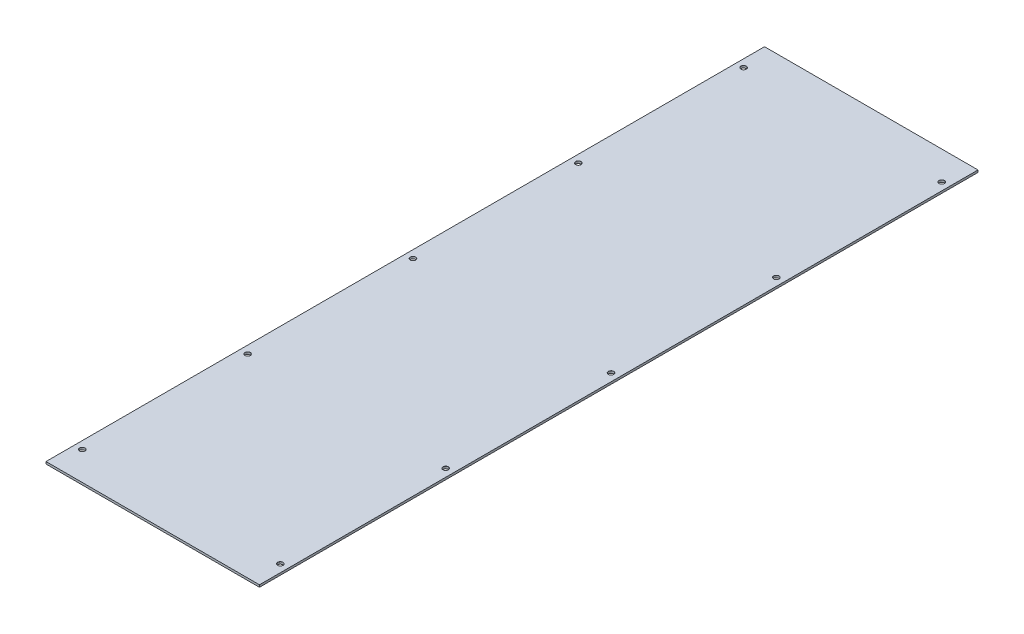
SolidWorks part; units mm, degrees
material "6061-T6 (SS)"
ref_plane "Front Plane" through (0, 0, 0) normal (0, 0, 1) x (1, 0, 0)
ref_plane "Top Plane" through (0, 0, 0) normal (0, 1, 0) x (1, 0, 0)
ref_plane "Right Plane" through (0, 0, 0) normal (1, 0, 0) x (0, 0, -1)
sketch "Sketch1" plane through (0, 0, 0) normal (0, 0, 1) x (1, 0, 0)
  line L1 (0, 0) -> (97, 0)
  line L2 (0, 0) -> (0, 1)
  line L3 (0, 1) -> (97, 1)
  line L4 (97, 0) -> (97, 1)
  dimension "D1" = 97
  dimension "D2" = 1
extrude "Boss-Extrude1" add sketch "Sketch1" along normal blind 326.5
hole_wizard "M2 Clearance Hole1" positions "Sketch2" profile "Sketch3" hole size "M2" standard "ISO" end condition through all
sketch "Sketch2" plane through (0, 1, 0) normal (0, 1, 0) x (1, 0, 0)
  line L0 (97, -326.5) -> (0, -326.5) construction
  line L1 (0, -326.5) -> (0, 0) construction
  line L2 (97, -326.5) -> (97, 0) construction
  point P0 (3.5, -313.5)
  point P2 (93.5, -313.5)
  point P21 (3.5, -238.375)
  point P22 (93.5, -238.375)
  point P23 (3.5, -163.25)
  point P24 (93.5, -163.25)
  point P25 (3.5, -88.125)
  point P26 (93.5, -88.125)
  point P27 (3.5, -13)
  point P28 (93.5, -13)
  dimension "D1" = 13
  dimension "D2" = 13
  dimension "D3" = 3.5
  dimension "D4" = 3.5
  dimension "D5" = 5
sketch "Sketch3" plane through (3.5, 1, 313.5) normal (1, 0, 0) x (0, 0, 1)
  line L0 (0, 0) -> (0, 1)
  line L1 (0, 1) -> (1.2, 1)
  line L2 (1.2, 1) -> (1.2, 0.025)
  line L3 (1.2, 0.025) -> (1.225, 0)
  line L5 (1.225, 0) -> (0, 0)
  line L6 (-1.2, 0.025) -> (-1.225, 0) construction
  line L11 (0, -6.35) -> (0, 107.95) construction
  dimension "Thru Hole Dia." = 2.4
  dimension "Thru Hole Depth" = 1
  dimension "Near C'Sink Dia." = 2.45
  dimension "Near C'Sink Angle" = 90
